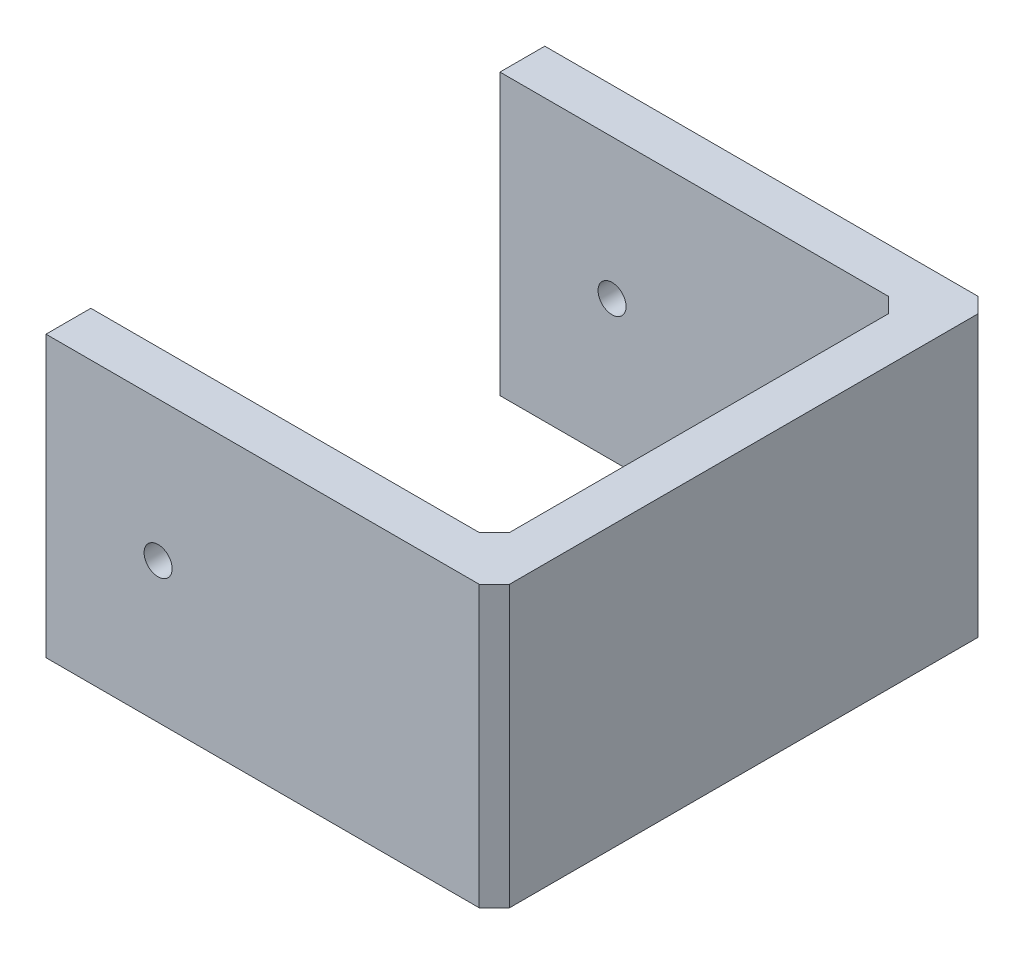
SolidWorks part; units mm, degrees
ref_plane "Front Plane" through (0, 0, 0) normal (0, 0, 1) x (1, 0, 0)
ref_plane "Top Plane" through (0, 0, 0) normal (0, 1, 0) x (1, 0, 0)
ref_plane "Right Plane" through (0, 0, 0) normal (1, 0, 0) x (0, 0, -1)
sketch "Sketch3" plane through (0, 0, 0) normal (0, 1, 0) x (1, 0, 0)
  line L0 (0, 18.25) -> (0, 22.25)
  line L1 (0, 22.25) -> (38.647, 22.25)
  line L3 (40, 20.897) -> (40, -20.897)
  line L5 (0, 18.25) -> (34.647, 18.25)
  line L7 (36, 16.897) -> (36, -16.897)
  line L8 (53.647, 0) -> (26.0091, 0) construction
  line L9 (0, -18.25) -> (0, -22.25)
  line L11 (0, -18.25) -> (34.647, -18.25)
  line L13 (0, -22.25) -> (38.647, -22.25)
  line L14 (34.647, 18.25) -> (36, 16.897)
  line L15 (36, -16.897) -> (34.647, -18.25)
  line L16 (40, -20.897) -> (38.647, -22.25)
  line L17 (38.647, 22.25) -> (40, 20.897)
  point P2 (0, 0)
  point P5 (42.7937, 25.0437)
  point P6 (0, 0)
  point P10 (38.7937, 21.0437)
  point P15 (38.7937, -21.0437)
  point P16 (49.647, 0)
  point P17 (42.7937, -25.0437)
  dimension "D1" = 4
  dimension "D2" = 4
  dimension "D4" = 40
  dimension "D6" = 5.6569
  dimension "D11" = 0
  dimension "D12" = 44.5
  dimension "D13" = 0
extrude "Boss-Extrude2" add sketch "Sketch3" along normal blind 25 contours L1 L17 L3 L16 L13 L9 L11 L15 L7 L14 L5 L0
sketch "Sketch6" plane through (0, 0, 22.25) normal (0, 0, 1) x (1, 0, 0)
  line L0 (0, 25) -> (0, 0) construction
  circle A0 centre (10, 12.5) radius 1.25
  dimension "D1" = 2.5
  dimension "D2" = 10
extrude "Cut-Extrude1" cut sketch "Sketch6" against normal through all
